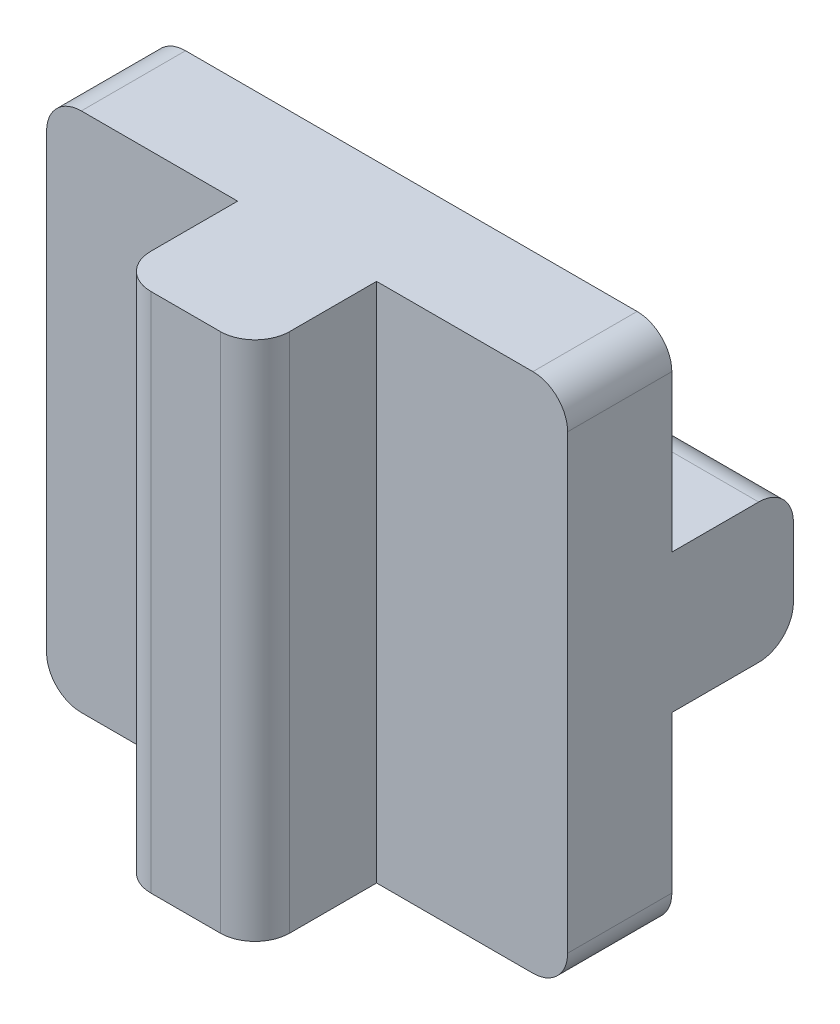
SolidWorks part; units mm, degrees
ref_plane "정면" through (0, 0, 0) normal (0, 0, 1) x (1, 0, 0)
ref_plane "윗면" through (0, 0, 0) normal (0, 1, 0) x (1, 0, 0)
ref_plane "우측면" through (0, 0, 0) normal (1, 0, 0) x (0, 0, -1)
sketch "스케치1" plane through (0, 0, 0) normal (0, 0, 1) x (1, 0, 0)
  line L0 (0, 0) -> (37.6104, 0) construction
  line L1 (0, 0) -> (0, 26.5408) construction
  line L3 (-15, -15) -> (15, -15)
  line L4 (-15, -15) -> (-15, 15)
  line L5 (-15, 15) -> (15, 15)
  line L6 (15, -15) -> (15, 15)
  line L7 (-15, -15) -> (15, 15) construction
  line L8 (-15, 15) -> (15, -15) construction
  dimension "D1" = 30
  dimension "D2" = 30
extrude "보스-돌출1" add sketch "스케치1" along normal blind 6
sketch "스케치2" plane through (0, 0, 0) normal (0, 0, -1) x (-1, 0, 0)
  line L4 (-15, 15) -> (-15, -15)
  line L5 (-15, -15) -> (15, -15)
  line L6 (15, -15) -> (15, 15)
  line L7 (15, 15) -> (-15, 15)
  line L8 (-15, 15) -> (-15, -15)
  line L9 (-15, -15) -> (15, -15)
  line L10 (15, -15) -> (15, 15)
  line L11 (15, 15) -> (-15, 15)
  line L12 (-15, 15) -> (15, 15)
  line L13 (-15, 15) -> (15, 15)
  line L14 (-15, -15) -> (-15, 15)
  line L15 (-15, -15) -> (-15, 15)
  line L16 (15, -15) -> (-15, -15)
  line L17 (15, -15) -> (-15, -15)
  line L18 (15, 15) -> (15, -15)
  line L19 (15, 15) -> (15, -15)
  line L21 (-15, -4) -> (15, -4)
  line L22 (-15, -4) -> (-15, 4)
  line L23 (-15, 4) -> (15, 4)
  line L24 (15, -4) -> (15, 4)
  line L25 (-15, -4) -> (15, 4) construction
  line L26 (-15, 4) -> (15, -4) construction
  point P2 (0, 0)
  dimension "D2" = 8
  dimension "D1" = 0
extrude "보스-돌출2" add sketch "스케치2" along normal blind 7 contours L23 L15 L21 L19
fillet "필렛1" radius 2 2 edges at (0, 4, -7) (0, -4, -7)
fillet "필렛2" radius 2 4 edges at (15, 15, 3) (-15, 15, 3) (-15, -15, 3) (15, -15, 3)
sketch "스케치3" plane through (0, 0, 6) normal (0, 0, 1) x (1, 0, 0)
  line L0 (-13, -15) -> (13, -15) construction
  line L1 (-4, 15) -> (4, 15)
  line L2 (-4, 15) -> (-4, -15)
  line L3 (-4, -15) -> (4, -15)
  line L4 (4, 15) -> (4, -15)
  line L5 (-4, 15) -> (4, -15) construction
  line L6 (-4, -15) -> (4, 15) construction
  point P0 (0, 0)
  dimension "D1" = 8
extrude "보스-돌출3" add sketch "스케치3" along normal blind 7
fillet "필렛3" radius 2 2 edges at (-4, 0, 13) (4, 0, 13)
